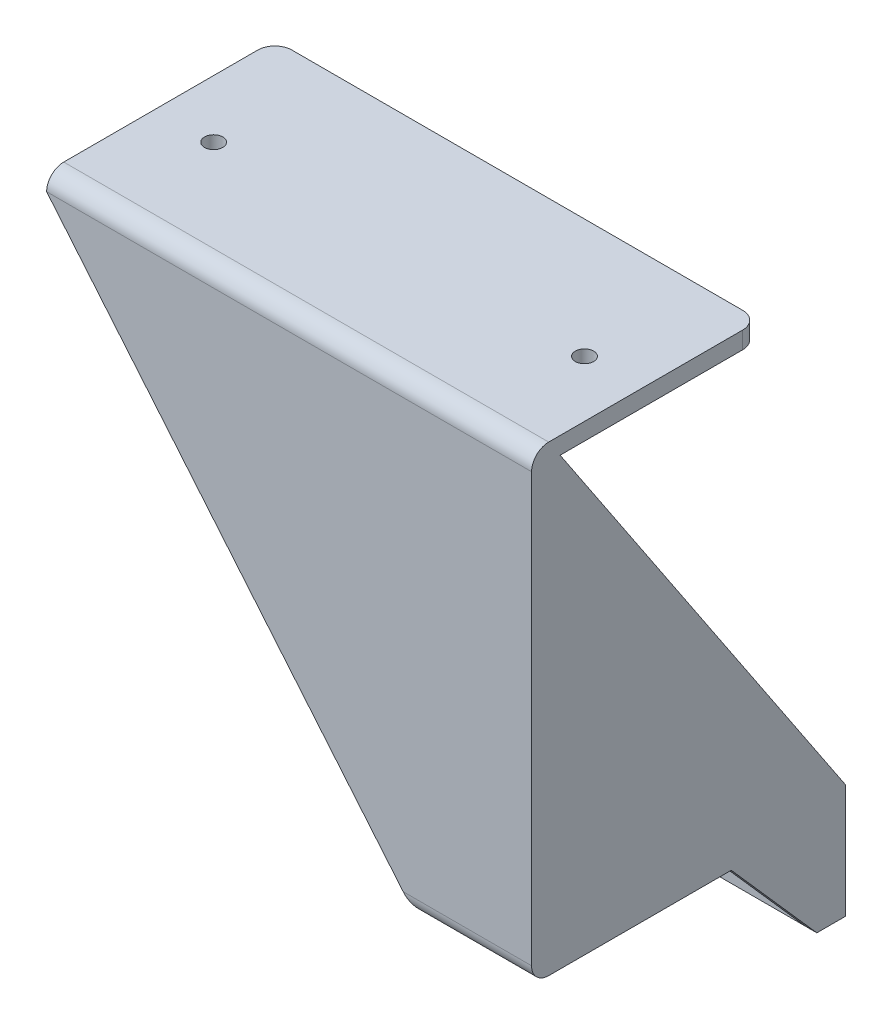
SolidWorks part; units mm, degrees
ref_plane "Front Plane" through (0, 0, 0) normal (0, 0, 1) x (1, 0, 0)
ref_plane "Top Plane" through (0, 0, 0) normal (0, 1, 0) x (1, 0, 0)
ref_plane "Right Plane" through (0, 0, 0) normal (1, 0, 0) x (0, 0, -1)
sketch "Sketch1" plane through (0, 0, 0) normal (0, 0, 1) x (1, 0, 0)
  line L1 (-10, -10) -> (10, -10)
  line L2 (-10, -10) -> (-10, 10)
  line L3 (-10, 10) -> (10, 10)
  line L4 (10, -10) -> (10, 10)
  line L5 (-10, -10) -> (10, 10) construction
  line L6 (-10, 10) -> (10, -10) construction
  point P0 (0, 0)
extrude "Boss-Extrude1" add sketch "Sketch1" along normal blind 5
sketch "Sketch2" plane through (0, 0, 0) normal (0, 0, 1) x (1, 0, 0)
  line L0 (10, -10) -> (10, 10) construction
  line L1 (-10, 10) -> (10, 10)
  line L2 (-10, 10) -> (-10, 7)
  line L3 (-10, 7) -> (10, 7)
  line L4 (10, 10) -> (10, 7)
extrude "Boss-Extrude2" add sketch "Sketch2" along normal blind 20
sketch "Sketch3" plane through (-10, 0, 0) normal (-1, 0, 0) x (0, 0, 1)
  line L0 (20, 7) -> (5, -10)
  line L1 (5, -10) -> (5, 7)
  line L2 (5, 7) -> (20, 7)
extrude "Boss-Extrude3" add sketch "Sketch3" against normal blind 2
sketch "Sketch4" plane through (10, 0, 0) normal (1, 0, 0) x (0, 0, -1)
  line L0 (-20, 7) -> (-5, -10)
  line L1 (-5, -10) -> (-5, 7)
  line L2 (-5, 7) -> (-20, 7)
extrude "Boss-Extrude4" add sketch "Sketch4" against normal blind 2
sketch "Sketch5" plane through (0, 0, 5) normal (0, 0, 1) x (1, 0, 0)
  line L1 (8, -10) -> (8, 7)
  circle A0 centre (0, -1.5) radius 2.6
extrude "Cut-Extrude1" cut sketch "Sketch5" against normal through all contours A0
sketch "Sketch6" plane through (0, 0, 20) normal (0, 0, 1) x (1, 0, 0)
  line L1 (-10, 10) -> (10, 10)
  line L2 (-10, 10) -> (-10, 7)
  line L3 (-10, 7) -> (10, 7)
  line L4 (10, 10) -> (10, 7)
extrude "Boss-Extrude5" add sketch "Sketch6" along normal blind 5
sketch "Sketch17" plane through (10, 0, 0) normal (1, 0, 0) x (0, 0, -1)
  line L1 (-25, 10) -> (-55, 10)
  line L2 (-25, 10) -> (-25, 7)
  line L3 (-25, 7) -> (-55, 7)
  line L4 (-55, 10) -> (-55, 7)
extrude "Boss-Extrude14" add sketch "Sketch17" against normal blind 20
sketch "Sketch18" plane through (10, 0, 0) normal (1, 0, 0) x (0, 0, -1)
  line L1 (-55, 10) -> (-42, 10)
  line L2 (-55, 10) -> (-55, 88)
  line L3 (-55, 88) -> (-42, 88)
  line L4 (-42, 10) -> (-42, 88)
extrude "Boss-Extrude17" add sketch "Sketch18" against normal blind 20
sketch "Sketch20" plane through (10, 0, 0) normal (1, 0, 0) x (0, 0, -1)
  line L3 (-42, 10) -> (-52, 10)
  line L4 (-52, 10) -> (-52, 88)
  line L5 (-42, 88) -> (-55, 88) construction
  line L6 (-52, 88) -> (-42, 88)
  line L7 (-42, 88) -> (-42, 10)
extrude "Cut-Extrude3" cut sketch "Sketch20" against normal through all
sketch "Sketch23" plane through (10, 0, 0) normal (1, 0, 0) x (0, 0, -1)
  line L0 (-52, 88) -> (0, 10)
  line L1 (-52, 88) -> (-52, 10)
  line L2 (-52, 10) -> (0, 10)
extrude "Boss-Extrude20" add sketch "Sketch23" against normal blind 2
sketch "Sketch24" plane through (0, 0, 52) normal (0, 0, -1) x (-1, 0, 0)
  line L0 (-10, 10) -> (-10, 88) construction
  line L1 (10, 88) -> (-10, 88)
  line L2 (10, 88) -> (10, 85)
  line L3 (10, 85) -> (-10, 85)
  line L4 (-10, 88) -> (-10, 85)
extrude "Boss-Extrude21" add sketch "Sketch24" along normal blind 42
sketch "Sketch25" plane through (-10, 0, 0) normal (-1, 0, 0) x (0, 0, 1)
  line L0 (55, 88) -> (55, 7) construction
  line L1 (10, 88) -> (55, 88)
  line L2 (10, 88) -> (10, 85)
  line L3 (10, 85) -> (55, 85)
  line L4 (55, 88) -> (55, 85)
extrude "Boss-Extrude22" add sketch "Sketch25" along normal blind 65
sketch "Sketch26" plane through (0, 88, 0) normal (0, 1, 0) x (1, 0, 0)
  line L0 (-75, -10) -> (-75, -15)
  line L1 (-75, -55) -> (-75, -10) construction
  line L2 (-75, -15) -> (10, -15)
  line L3 (10, -10) -> (10, -55) construction
  line L4 (10, -15) -> (10, -10)
  line L5 (10, -10) -> (-75, -10)
extrude "Cut-Extrude4" cut sketch "Sketch26" against normal blind 28
sketch "Sketch27" plane through (0, 0, 55) normal (0, 0, 1) x (1, 0, 0)
  line L0 (-75, 85) -> (-10, 7)
  line L1 (-10, 7) -> (-10, 85)
  line L2 (-10, 85) -> (-75, 85)
extrude "Boss-Extrude24" add sketch "Sketch27" against normal blind 3
sketch "Sketch28" plane through (0, 88, 0) normal (0, 1, 0) x (1, 0, 0)
  circle A0 centre (0.1205, -35.8462) radius 1.6
  circle A1 centre (-64.8795, -35.8462) radius 1.6
extrude "Cut-Extrude6" cut sketch "Sketch28" against normal blind 7
fillet "Fillet4" radius 3 2 edges at (10, 86.5, 15) (-75, 86.5, 15)
fillet "Fillet5" radius 3 2 edges at (0, 7, 55) (-32.5, 88, 55)
